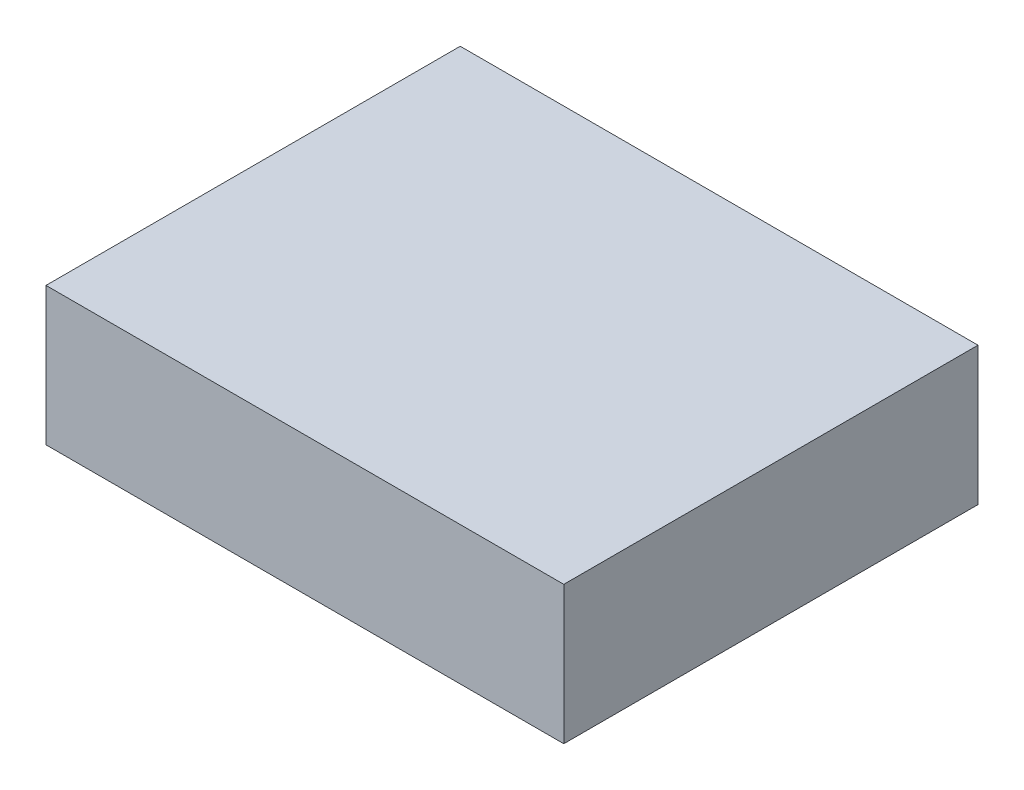
SolidWorks part; units mm, degrees
ref_plane "Front Plane" through (0, 0, 0) normal (0, 0, 1) x (1, 0, 0)
ref_plane "Top Plane" through (0, 0, 0) normal (0, 1, 0) x (1, 0, 0)
ref_plane "Right Plane" through (0, 0, 0) normal (1, 0, 0) x (0, 0, -1)
sketch "Sketch1" plane through (0, 0, 0) normal (0, 1, 0) x (1, 0, 0)
  line L1 (-19.05, -15.24) -> (19.05, -15.24)
  line L2 (-19.05, -15.24) -> (-19.05, 15.24)
  line L3 (-19.05, 15.24) -> (19.05, 15.24)
  line L4 (19.05, -15.24) -> (19.05, 15.24)
  line L5 (-19.05, -15.24) -> (19.05, 15.24) construction
  line L6 (-19.05, 15.24) -> (19.05, -15.24) construction
  point P0 (0, 0)
  dimension "D1" = 38.1
  dimension "D2" = 30.48
extrude "Boss-Extrude1" add sketch "Sketch1" along normal blind 10.16 contours L2 L3 L4 L1
sketch "Sketch3" plane through (0, 0, 0) normal (0, -1, 0) x (1, 0, 0)
  line L0 (0, 15.24) -> (0, 0) construction
  line L1 (-19.05, 15.24) -> (19.05, 15.24) construction
  line L2 (0, 0) -> (0, -15.24) construction
  line L3 (-19.05, -15.24) -> (19.05, -15.24) construction
  circle A0 centre (0, 7.62) radius 1.65
  circle A1 centre (0, -7.62) radius 1.65
  dimension "D1" = 3.3
  dimension "D2" = 3.3
extrude "Cut-Extrude1" cut sketch "Sketch3" against normal blind 10
